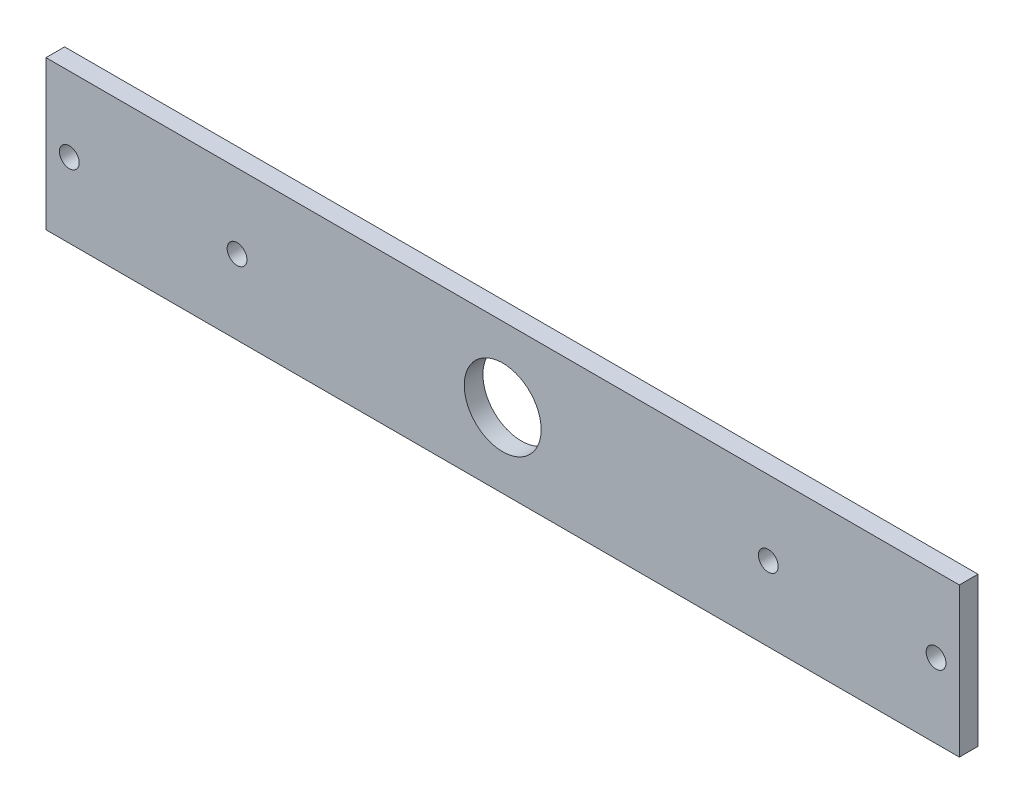
SolidWorks part; units mm, degrees
ref_plane "Front" through (0, 0, 0) normal (0, 0, 1) x (1, 0, 0)
ref_plane "Top" through (0, 0, 0) normal (0, 1, 0) x (1, 0, 0)
ref_plane "Right" through (0, 0, 0) normal (1, 0, 0) x (0, 0, -1)
sketch "Sketch1" plane through (0, 0, 0) normal (0, 0, 1) x (1, 0, 0)
  line L1 (-155.575, -25.4) -> (155.575, -25.4)
  line L2 (-155.575, -25.4) -> (-155.575, 25.4)
  line L3 (-155.575, 25.4) -> (155.575, 25.4)
  line L4 (155.575, -25.4) -> (155.575, 25.4)
  line L5 (-155.575, -25.4) -> (155.575, 25.4) construction
  line L6 (-155.575, 25.4) -> (155.575, -25.4) construction
  point P0 (0, 0)
  dimension "D1" = 50.8
  dimension "D2" = 311.15
extrude "Boss-Extrude1" add sketch "Sketch1" along normal blind 6.35
sketch "Sketch3" plane through (0, 0, 6.35) normal (0, 0, 1) x (1, 0, 0)
  line L0 (0, 0) -> (-90.4875, 0) construction
  line L1 (-90.4875, 0) -> (-147.6375, 0) construction
  point P0 (0, 0)
  point P4 (-119.0625, 0)
  dimension "D1" = 119.0625
  dimension "D2" = 57.15
hole_wizard "1 Clearance Hole1" positions "Sketch5" profile "Sketch4" hole size "1" standard "ANSI Inch" end condition through all
sketch "Sketch5" plane through (0, 0, 6.35) normal (0, 0, 1) x (1, 0, 0)
  point P0 (0, 0)
sketch "Sketch4" plane through (0, 0, 6.35) normal (1, 0, 0) x (0, -1, 0)
  line L0 (0, 0) -> (0, 6.35)
  line L1 (0, 6.35) -> (13.0962, 6.35)
  line L2 (13.0962, 6.35) -> (13.0962, 0)
  line L5 (13.0962, 0) -> (0, 0)
  line L11 (0, -6.35) -> (0, 107.95) construction
  dimension "Thru Hole Dia." = 26.1925
  dimension "Thru Hole Depth" = 6.35
hole_wizard "1/4 Clearance Hole1" positions "Sketch7" profile "Sketch6" hole size "1/4" standard "ANSI Inch" end condition through all
sketch "Sketch7" plane through (0, 0, 6.35) normal (0, 0, 1) x (1, 0, 0)
  point P0 (-147.6375, 0)
  point P3 (-90.4875, 0)
sketch "Sketch6" plane through (-147.6375, 0, 6.35) normal (1, 0, 0) x (0, -1, 0)
  line L0 (0, 0) -> (0, 6.35)
  line L1 (0, 6.35) -> (3.3782, 6.35)
  line L2 (3.3782, 6.35) -> (3.3782, 0)
  line L5 (3.3782, 0) -> (0, 0)
  line L11 (0, -6.35) -> (0, 107.95) construction
  dimension "Thru Hole Dia." = 6.7564
  dimension "Thru Hole Depth" = 6.35
mirror "Mirror1" about plane through (0, 0, 0) normal (1, 0, 0) of "1/4 Clearance Hole1"
